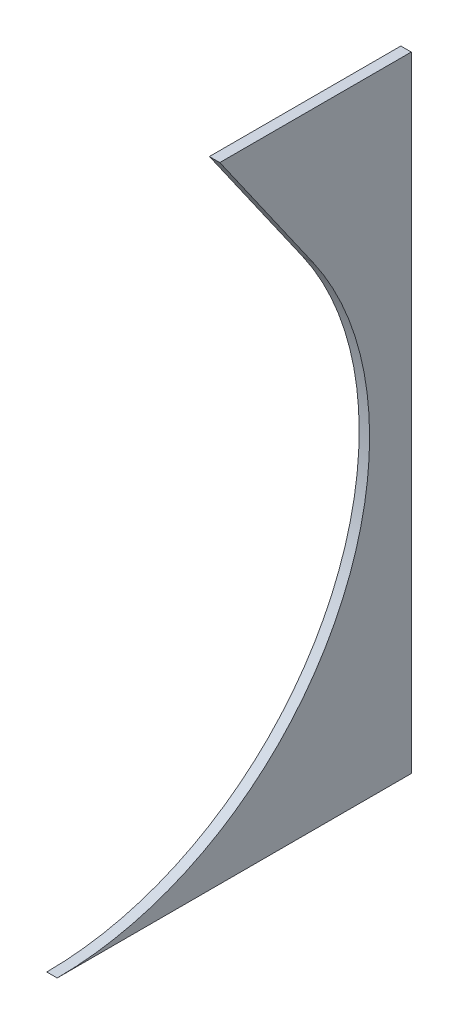
SolidWorks part; units mm, degrees
ref_plane "Front Plane" through (0, 0, 0) normal (0, 0, 1) x (1, 0, 0)
ref_plane "Top Plane" through (0, 0, 0) normal (0, 1, 0) x (1, 0, 0)
ref_plane "Right Plane" through (0, 0, 0) normal (1, 0, 0) x (0, 0, -1)
sketch "Sketch1" plane through (0, 0, 0) normal (1, 0, 0) x (0, 0, -1)
  line L0 (-95.25, 22.4118) -> (120.65, 22.4118) construction
  line L1 (-95.25, -168.0882) -> (120.65, -168.0882)
  line L2 (-95.25, -168.0882) -> (-95.25, 212.9118)
  line L3 (-95.25, 212.9118) -> (120.65, 212.9118)
  line L4 (120.65, -168.0882) -> (120.65, 212.9118)
  line L5 (-95.25, -168.0882) -> (120.65, 212.9118) construction
  line L6 (-95.25, 212.9118) -> (120.65, -168.0882) construction
  point P0 (0, 0)
  dimension "D1" = 215.9
  dimension "D2" = 381
extrude "Boss-Extrude1" add sketch "Sketch1" along normal blind 6.35
sketch "Sketch2" plane through (6.35, 0, 0) normal (1, 0, 0) x (0, 0, -1)
  line L0 (-95.25, 212.9118) -> (-95.25, -168.0882) construction
  line L1 (120.65, 212.9118) -> (-95.25, 212.9118) construction
  circle A0 centre (-95.25, 22.4118) radius 190.5
  dimension "D1" = 381
  dimension "D2" = 0
  dimension "D3" = 190.5
extrude "Cut-Extrude1" cut sketch "Sketch2" against normal through all
sketch "Sketch3" plane through (6.35, 0, 0) normal (1, 0, 0) x (0, 0, -1)
  line L1 (60.7985, 131.6781) -> (-18.9682, 245.5967)
  line L2 (60.7985, 131.6781) -> (-203.4462, 131.6781)
  line L5 (-18.9682, 245.5967) -> (-203.4462, 245.5967)
  line L6 (-203.4462, 245.5967) -> (-203.4462, 131.6781)
  arc A0 (-95.25, -168.0882) -> (-95.25, 212.9118) centre (-95.25, 22.4118) ccw construction
  dimension "D1" = 55
extrude "Cut-Extrude2" cut sketch "Sketch3" against normal through all
